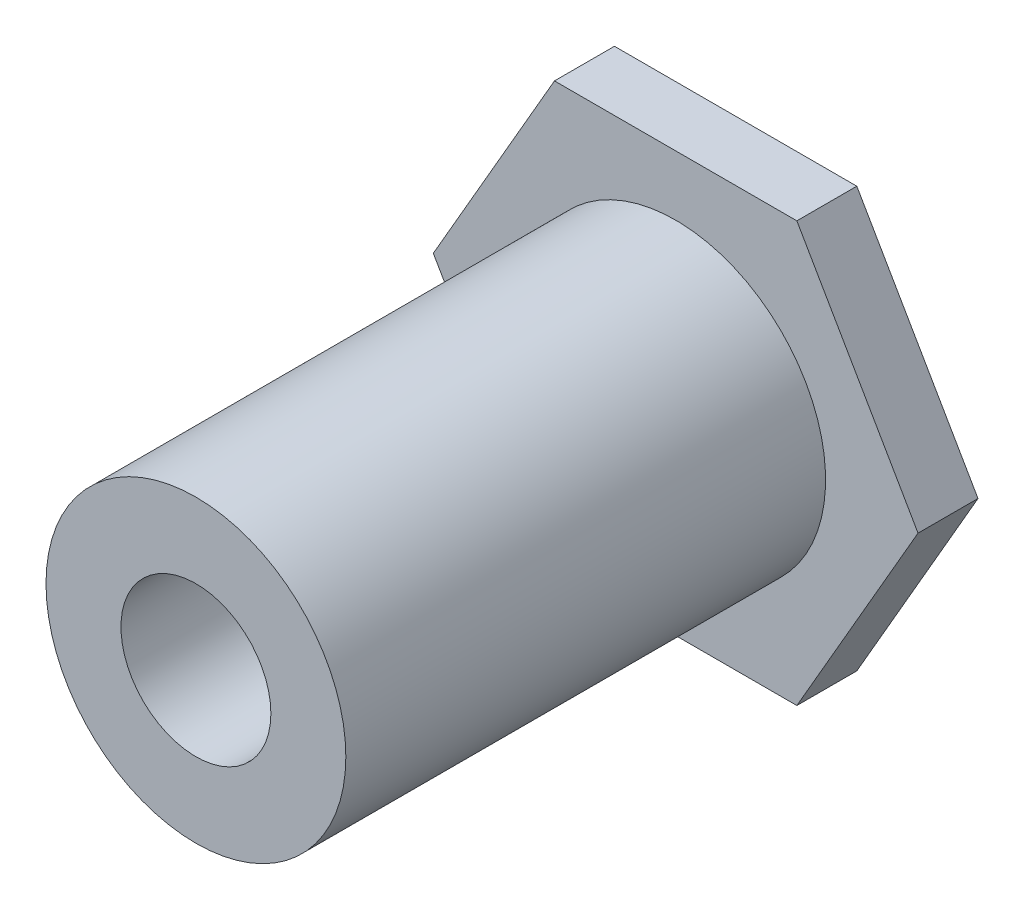
SolidWorks part; units mm, degrees
ref_plane "前视基准面" through (0, 0, 0) normal (0, 0, 1) x (1, 0, 0)
ref_plane "上视基准面" through (0, 0, 0) normal (0, 1, 0) x (1, 0, 0)
ref_plane "右视基准面" through (0, 0, 0) normal (1, 0, 0) x (0, 0, -1)
sketch "草图1" plane through (0, 0, 0) normal (0, 0, 1) x (1, 0, 0)
  circle A0 centre (0, 0) radius 1.25
  circle A1 centre (0, 0) radius 2.5
  dimension "内径" = 2.5
  dimension "外径" = 5
extrude "凸台-拉伸1" add sketch "草图1" along normal blind 8
sketch "草图2" plane through (0, 0, 0) normal (0, 0, -1) x (-1, 0, 0)
  line L1 (-2.0207, -3.5) -> (2.0207, -3.5)
  line L2 (2.0207, -3.5) -> (4.0415, 0)
  line L3 (4.0415, 0) -> (2.0207, 3.5)
  line L4 (2.0207, 3.5) -> (-2.0207, 3.5)
  line L5 (-2.0207, 3.5) -> (-4.0415, 0)
  line L6 (-4.0415, 0) -> (-2.0207, -3.5)
  circle A1 centre (0, 0) radius 3.5 construction
  dimension "外径" = 7
extrude "凸台-拉伸2" add sketch "草图2" along normal blind 1
